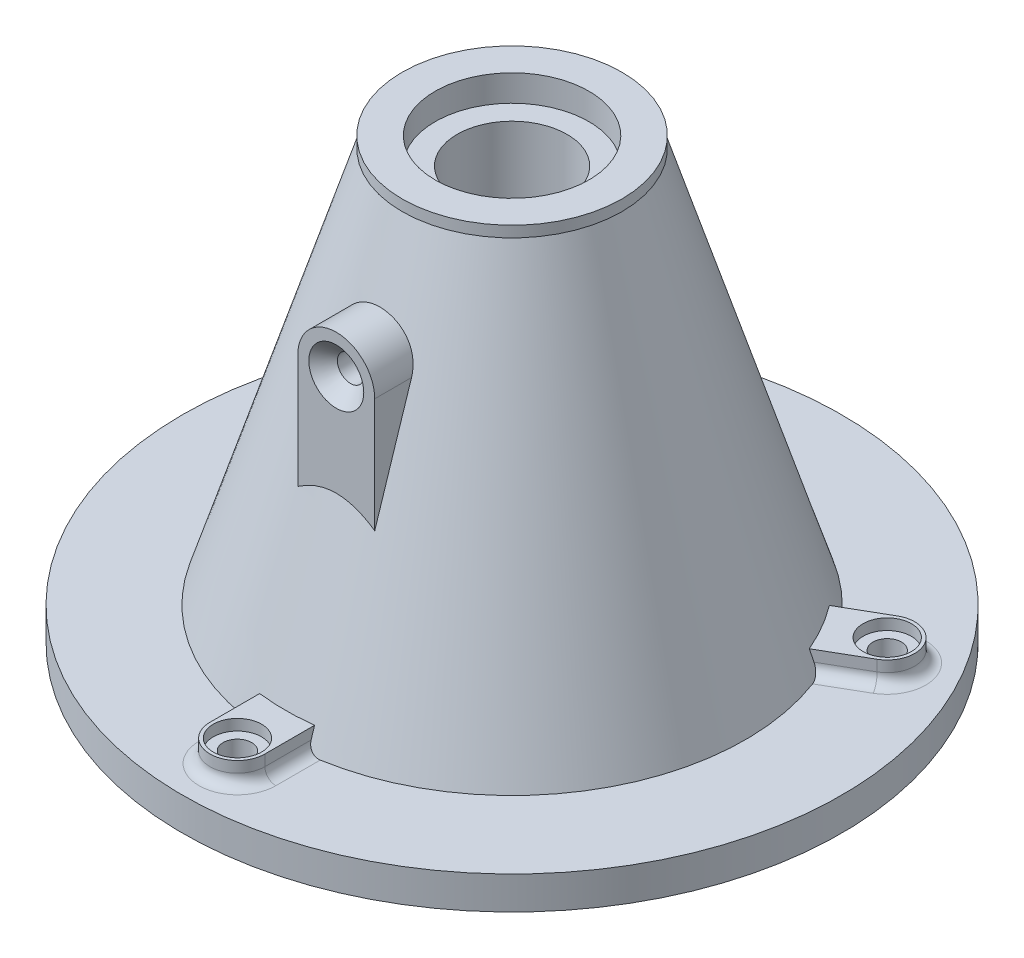
SolidWorks part; units mm, degrees
ref_plane "Front Plane" through (0, 0, 0) normal (0, 0, 1) x (1, 0, 0)
ref_plane "Top Plane" through (0, 0, 0) normal (0, 1, 0) x (1, 0, 0)
ref_plane "Right Plane" through (0, 0, 0) normal (1, 0, 0) x (0, 0, -1)
sketch "Sketch1" plane through (0, 0, 0) normal (0, 0, 1) x (1, 0, 0)
  line L0 (-150, 0) -> (-150, 15)
  line L1 (-150, 15) -> (-106.2655, 15)
  line L3 (-50, 200) -> (0, 200)
  line L4 (0, 200) -> (0, 0)
  line L5 (0, 0) -> (-150, 0)
  line L6 (-90, 0) -> (-70.2427, 63.2058) construction
  line L7 (-106.2655, 15) -> (-50, 195)
  line L8 (-50, 195) -> (-50, 200)
  point P9 (0, 0)
  point P10 (0, 0)
  dimension "D1" = 150
  dimension "D2" = 50
  dimension "D3" = 200
  dimension "D4" = 15
  dimension "D5" = 20
  dimension "D6" = 5
  dimension "D7" = 90
revolve "Revolve1" add sketch "Sketch1" angle 360 about L4
sketch "Sketch2" plane through (0, 0, 0) normal (0, 0, 1) x (1, 0, 0)
  line L0 (50, 200) -> (-50, 200) construction
  line L1 (-17.5, 145) -> (-17.5, 90)
  line L2 (-17.5, 90) -> (17.5, 90)
  line L3 (17.5, 90) -> (17.5, 145)
  arc A0 (17.5, 145) -> (-17.5, 145) centre (0, 145) ccw
  point P6 (0, 0)
  dimension "D1" = 35
  dimension "D2" = 55
  dimension "D3" = 55
extrude "Boss-Extrude1" add sketch "Sketch2" along normal blind 80
sketch "Sketch4" plane through (0, 0, 0) normal (1, 0, 0) x (0, 0, -1)
  line L0 (-80, 145) -> (0, 145) construction
  line L1 (0, 151) -> (-73.5, 151)
  line L2 (-73.5, 151) -> (-80, 157.5)
  line L3 (-80, 157.5) -> (-80, 145)
  line L4 (-80, 145) -> (0, 145)
  line L5 (0, 145) -> (0, 151)
  point P3 (-0.4953, 145)
  dimension "D1" = 6.5
  dimension "D2" = 6
  dimension "D3" = 45
revolve "Cut-Revolve1" cut sketch "Sketch4" angle 360 about L0
hole_wizard "Hole1" positions "Sketch5" profile "Sketch6" legacy end condition through all
sketch "Sketch5" plane through (0, 200, 0) normal (0, 1, 0) x (1, 0, 0)
  point P0 (0, 0)
sketch "Sketch6" plane through (0, 200, 0) normal (1, 0, 0) x (0, 0, 1)
  line L0 (0, 0) -> (0, 200)
  line L1 (0, 200) -> (25, 200)
  line L2 (25, 200) -> (25, 12)
  line L3 (25, 12) -> (35, 12)
  line L4 (35, 12) -> (35, 0)
  line L5 (35, 0) -> (0, 0)
  line L6 (0, 110) -> (0, -10) construction
  dimension "Diameter" = 50
  dimension "Depth" = 200
  dimension "C-Bore Diameter" = 70
  dimension "C-Bore Depth" = 12
sketch "Sketch7" plane through (0, 0, 0) normal (1, 0, 0) x (0, 0, -1)
  line L0 (0, 0) -> (90, 0)
  line L1 (-150, 0) -> (150, 0) construction
  line L2 (90, 0) -> (53.9317, 115.3868)
  line L4 (38.6604, 115.3868) -> (26.9738, 78)
  line L5 (26.9738, 78) -> (0, 78)
  line L6 (0, 78) -> (0, 0)
  line L7 (106.2655, 15) -> (50, 195) construction
  arc A0 (53.9317, 115.3868) -> (38.6604, 115.3868) centre (46.296, 113) ccw
  point P6 (0, 0)
  point P14 (42.5229, 120.0543)
  dimension "D1" = 16
  dimension "D2" = 113
  dimension "D3" = 78
  dimension "D4" = 20
revolve "Cut-Revolve2" cut sketch "Sketch7" angle 360 about L6
sketch "Sketch10" plane through (0, 15, 0) normal (0, 1, 0) x (1, 0, 0)
  line L0 (-12.5, -125) -> (-12.5, -100)
  line L1 (-12.5, -100) -> (12.5, -100)
  line L2 (12.5, -100) -> (12.5, -125)
  arc A0 (-12.5, -125) -> (12.5, -125) centre (0, -125) ccw
  point P1 (0, 0)
  dimension "D1" = 25
  dimension "D2" = 125
  dimension "D3" = 100
extrude "Boss-Extrude2" add sketch "Sketch10" along normal blind 10
pattern_circular "CirPattern1" count 3 over 360 about axis through (0, 0, 0) along (0, 1, 0) of "Boss-Extrude2"
fillet "Fillet1" radius 5 9 edges at (93.5715, 15, -68.4573) (119.0785, 15, -68.75) (12.5, 15, 115.2639) (0, 15, 137.5) (-93.5715, 15, -68.4573) (-119.0785, 15, -68.75) (106.0715, 15, -46.8066) (-12.5, 15, 115.2639) (-106.0715, 15, -46.8066)
hole_wizard "Hole2" positions "Sketch11" profile "Sketch12" legacy end condition through all
sketch "Sketch11" plane through (0, 25, 0) normal (0, 1, 0) x (1, 0, 0)
  point P0 (108.2532, 62.5)
  point P3 (-108.2532, 62.5)
  point P6 (0, -125)
sketch "Sketch12" plane through (108.2532, 25, -62.5) normal (1, 0, 0) x (0, 0, 1)
  line L0 (0, 0) -> (0, 25)
  line L1 (0, 25) -> (6.5, 25)
  line L2 (6.5, 25) -> (6.5, 5)
  line L3 (6.5, 5) -> (11, 5)
  line L4 (11, 5) -> (11, 0)
  line L5 (11, 0) -> (0, 0)
  line L6 (0, 110) -> (0, -10) construction
  dimension "Diameter" = 13
  dimension "Depth" = 25
  dimension "C-Bore Diameter" = 22
  dimension "C-Bore Depth" = 5
